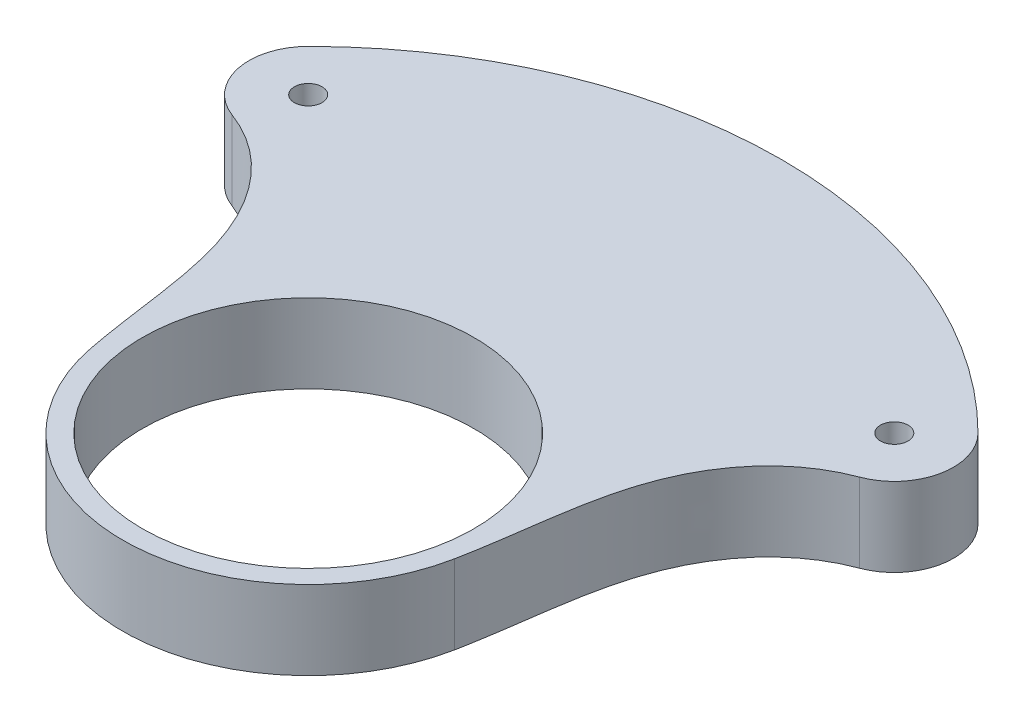
SolidWorks part; units mm, degrees
ref_plane "Front Plane" through (0, 0, 0) normal (0, 0, 1) x (1, 0, 0)
ref_plane "Top Plane" through (0, 0, 0) normal (0, 1, 0) x (1, 0, 0)
ref_plane "Right Plane" through (0, 0, 0) normal (1, 0, 0) x (0, 0, -1)
sketch "Sketch2" plane through (0, 0, 0) normal (0, 1, 0) x (1, 0, 0)
  line L0 (-31.8198, 31.8198) -> (-42.4264, 42.4264)
  line L1 (0, -55) -> (0, 55) construction
  line L2 (23.5, 0) -> (45, 0) construction
  circle A0 centre (0, 0) radius 45 construction
  circle A1 centre (0, 0) radius 60
  arc A2 (-42.4264, 42.4264) -> (-31.8198, 31.8198) centre (-37.1231, 37.1231) ccw
  arc A3 (42.4264, 42.4264) -> (31.8198, 31.8198) centre (37.1231, 37.1231) cw
  circle A4 centre (0, 0) radius 21
  circle A5 centre (0, 0) radius 23.5
  circle A6 centre (0, 0) radius 34.25 construction
  spline S0 degree 3 poles (-39.742, 30.0952) (-34.3086, 28.0705) (-24.8133, 17.3718) (-24.7508, 4.0744) (-23.0586, -4.5332) knots 0 0 0 0 0.392293 1 1 1 1
  spline S1 degree 3 poles (39.742, 30.0952) (34.3086, 28.0705) (24.8133, 17.3718) (24.7508, 4.0744) (23.0586, -4.5332) knots 0 0 0 0 0.392293 1 1 1 1
  point P23 (34.25, 0)
  point P24 (0, 0)
  point P25 (-26.1616, 20.114)
  point P26 (-26.9114, 19.0991)
  point P27 (-26.2439, 17.8695)
  dimension "D2" = 120
  dimension "D4" = 42
  dimension "D1" = 15
  dimension "D3" = 45
  dimension "D5" = 2.5
extrude "Boss-Extrude1" add sketch "Sketch2" along normal blind 10
sketch "Sketch3" plane through (0, 10, 0) normal (0, 1, 0) x (1, 0, 0)
  line L0 (0, 0) -> (-37.1231, 37.1231) construction
  line L1 (-37.1231, 37.1231) -> (37.1231, 37.1231) construction
  line L2 (37.1231, 37.1231) -> (0, 0) construction
  line L3 (0, -55) -> (0, 55) construction
  circle A0 centre (-37.1231, 37.1231) radius 1.75
  circle A1 centre (37.1231, 37.1231) radius 1.75
  dimension "D1" = 3.5
extrude "Cut-Extrude1" cut sketch "Sketch3" against normal up to next
equation "\"Width\"= 10mm"
equation "\"Thick\"= 10mm"
equation "\"Diameter\"=120"
equation "\"D2@Sketch2\"= \"Diameter\""
equation "\"DegreeOfArc\"= 90deg"
equation "\"D3@Sketch2\"= \"DegreeOfArc\" / 2"
equation "\"D1@Boss-Extrude1\"= \"Thick\""
equation "\"D1@Sketch2\"=\"Width\"*1.5"
equation "\"D4@Sketch2\"=42"
